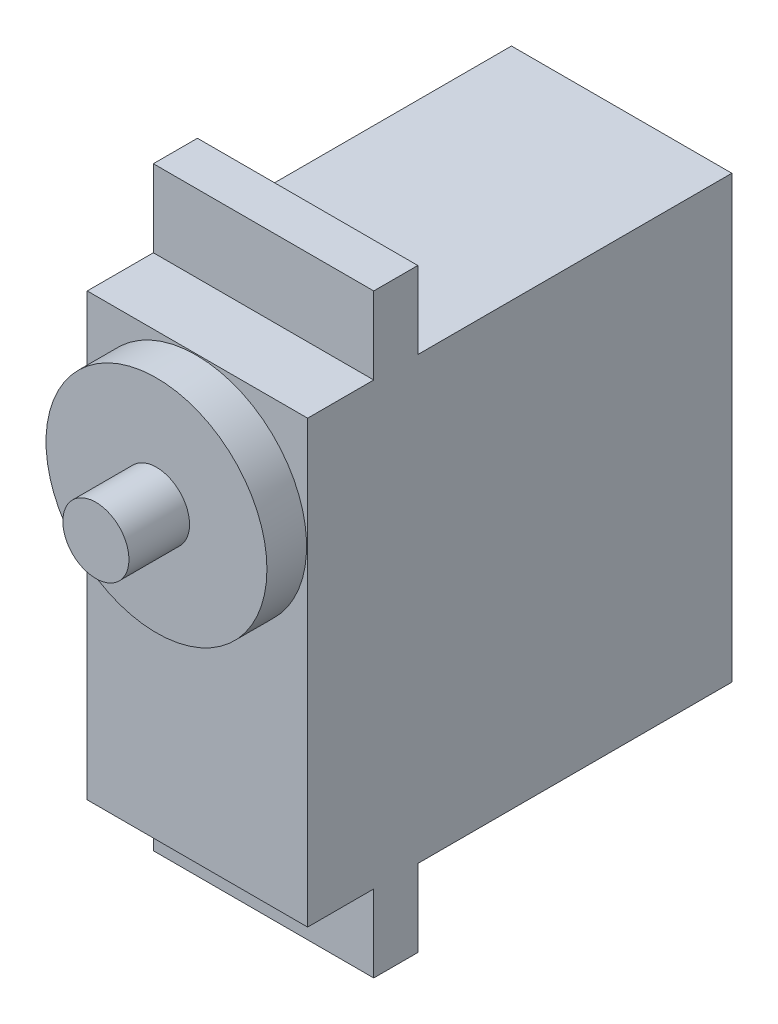
SolidWorks part; units mm, degrees
ref_plane "Alzado" through (0, 0, 0) normal (1, 0, 0) x (0, 1, 0)
ref_plane "Planta" through (0, 0, 0) normal (0, 0, 1) x (0, 1, 0)
ref_plane "Vista lateral" through (0, 0, 0) normal (0, 1, 0) x (-1, 0, 0)
sketch "Croquis1" plane through (0, 0, 0) normal (0, 0, 1) x (0, 1, 0)
  line L1 (-27, 10) -> (27, 10)
  line L2 (-27, 10) -> (-27, -10)
  line L3 (-27, -10) -> (27, -10)
  line L4 (27, 10) -> (27, -10)
  line L5 (-27, 10) -> (27, -10) construction
  line L6 (-27, -10) -> (27, 10) construction
  point P0 (0, 0)
extrude "Saliente-Extruir1" add sketch "Croquis1" along normal blind 4
sketch "Croquis2" plane through (0, 0, 4) normal (0, 0, 1) x (1, 0, 0)
  line L0 (-10, 27) -> (-10, -27) construction
  line L1 (-10, 20) -> (10, 20)
  line L2 (-10, 20) -> (-10, -20)
  line L3 (-10, -20) -> (10, -20)
  line L4 (10, 20) -> (10, -20)
  line L5 (10, -27) -> (10, 27) construction
extrude "Saliente-Extruir2" add sketch "Croquis2" along normal blind 6
sketch "Croquis3" plane through (0, 0, 10) normal (0, 0, 1) x (1, 0, 0)
  circle A1 centre (-0.1162, 9.8844) radius 10.024
extrude "Saliente-Extruir3" add sketch "Croquis3" along normal blind 3.6
sketch "Croquis4" plane through (0, 0, 13.6) normal (0, 0, 1) x (1, 0, 0)
  circle A0 centre (-0.1162, 9.8844) radius 3
extrude "Saliente-Extruir4" add sketch "Croquis4" along normal blind 5.5
sketch "Croquis5" plane through (0, 0, 0) normal (0, 0, -1) x (1, 0, 0)
  line L0 (-10, -27) -> (-10, 27) construction
  line L1 (-10, 20) -> (10, 20)
  line L2 (-10, 20) -> (-10, -20)
  line L3 (-10, -20) -> (10, -20)
  line L4 (10, 20) -> (10, -20)
extrude "Saliente-Extruir5" add sketch "Croquis5" along normal blind 28.5
